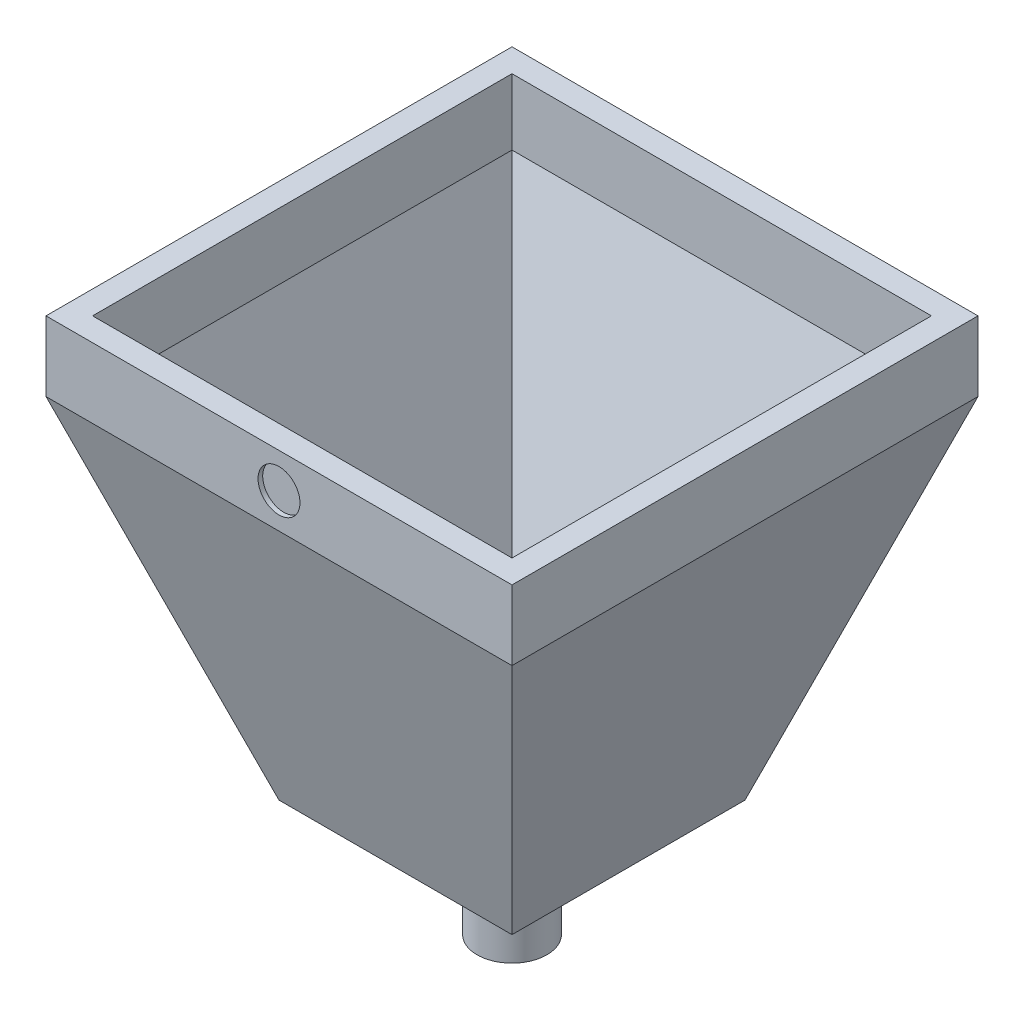
SolidWorks part; units mm, degrees
ref_plane "Alzado" through (0, 0, 0) normal (0, 0, 1) x (1, 0, 0)
ref_plane "Planta" through (0, 0, 0) normal (0, 1, 0) x (1, 0, 0)
ref_plane "Vista lateral" through (0, 0, 0) normal (1, 0, 0) x (0, 0, -1)
sketch "Croquis1" plane through (0, 0, 0) normal (0, 1, 0) x (1, 0, 0)
  line L1 (-5, -5) -> (5, -5)
  line L2 (-5, -5) -> (-5, 5)
  line L3 (-5, 5) -> (5, 5)
  line L4 (5, -5) -> (5, 5)
  line L5 (-5, -5) -> (5, 5) construction
  line L6 (-5, 5) -> (5, -5) construction
  point P0 (0, 0)
  dimension "D1" = 10
  dimension "D2" = 10
ref_plane "Plano1" through (0, 15, 0) normal (0, 1, 0) x (1, 0, 0)
sketch "Croquis2" plane through (0, 15, 0) normal (0, 1, 0) x (1, 0, 0)
  line L1 (-10, -10) -> (10, -10)
  line L2 (-10, -10) -> (-10, 10)
  line L3 (-10, 10) -> (10, 10)
  line L4 (10, -10) -> (10, 10)
  line L5 (-10, -10) -> (10, 10) construction
  line L6 (-10, 10) -> (10, -10) construction
  point P0 (0, 0)
  dimension "D1" = 20
  dimension "D2" = 20
loft "Recubrir1" add profiles "Croquis2", "Croquis1"
sketch "Croquis3" plane through (0, 15, 0) normal (0, 1, 0) x (1, 0, 0)
  line L1 (10, -10) -> (-10, -10)
  line L2 (10, -10) -> (10, 10)
  line L3 (10, 10) -> (-10, 10)
  line L4 (-10, -10) -> (-10, 10)
  line L5 (10, -10) -> (-10, 10) construction
  line L6 (10, 10) -> (-10, -10) construction
  point P0 (0, 0)
extrude "Saliente-Extruir1" add sketch "Croquis3" along normal blind 3
shell "Vaciado2" thickness 1
sketch "Croquis4" plane through (0, 0, 0) normal (0, -1, 0) x (-1, 0, 0)
  circle A0 centre (0, 0) radius 1.5
  dimension "D1" = 3
extrude "Cortar-Extruir1" cut sketch "Croquis4" against normal blind 3
sketch "Croquis5" plane through (0, 0, 0) normal (0, -1, 0) x (-1, 0, 0)
  circle A0 centre (0, 0) radius 1.5
extrude "Saliente-Extruir2" add sketch "Croquis5" along normal blind 5 separate body
sketch "Croquis6" plane through (0, -5, 0) normal (0, -1, 0) x (-1, 0, 0)
  circle A0 centre (0, 0) radius 1.3559
extrude "Cortar-Extruir2" cut sketch "Croquis6" against normal blind 15
sketch "Croquis7" plane through (0, 0, 0) normal (1, 0, 0) x (0, 0, -1)
  circle A0 centre (0, -2.4392) radius 1
  dimension "D1" = 2
extrude "Saliente-Extruir4" add sketch "Croquis7" along normal blind 1.5
ref_plane "Plano4" through (1.5, 0, 0) normal (1, 0, 0) x (0, 0, -1)
sketch "Croquis10" plane through (0, 0, 0) normal (0, -1, 0) x (-1, 0, 0)
  circle A0 centre (0, 0) radius 1.4064
extrude "Cortar-Extruir3" cut sketch "Croquis10" against normal blind 1.5 and the other way blind 31.5
ref_plane "Plano5" through (0, 0, -10) normal (0, 0, -1) x (-1, 0, 0)
sketch "Croquis11" plane through (0, 0, -10) normal (0, 0, -1) x (-1, 0, 0)
  circle A0 centre (0, 16.5) radius 0.9
  dimension "D1" = 1.8
extrude "Cortar-Extruir4" cut sketch "Croquis11" against normal blind 0.2 contours A0
ref_plane "Plano8" through (0, 0, 10) normal (0, 0, 1) x (1, 0, 0)
sketch "Croquis12" plane through (0, 0, 10) normal (0, 0, 1) x (1, 0, 0)
  circle A0 centre (0, 16.5) radius 0.9
  dimension "D1" = 1.8
sketch "Croquis14" plane through (0, 0, 10) normal (0, 0, 1) x (1, 0, 0)
extrude "Cortar-Extruir5" cut sketch "Croquis12" against normal blind 0.2
